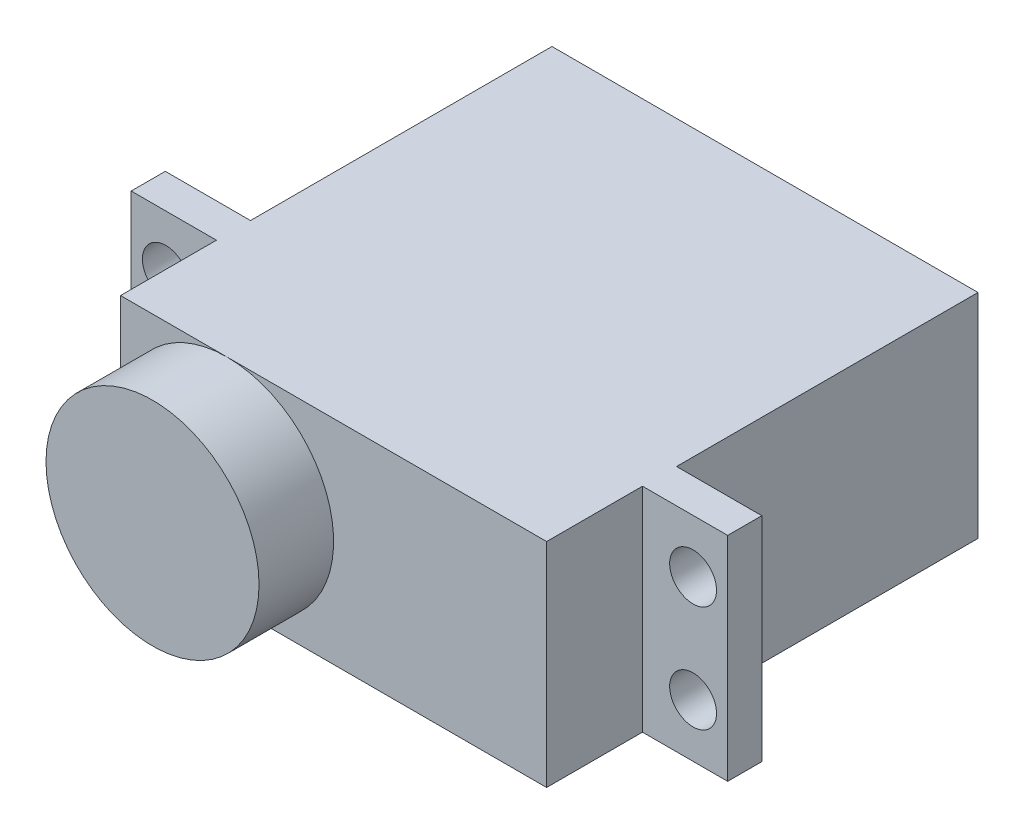
SolidWorks part; units mm, degrees
ref_plane "Front Plane" through (0, 0, 0) normal (0, 0, 1) x (1, 0, 0)
ref_plane "Top Plane" through (0, 0, 0) normal (0, 1, 0) x (1, 0, 0)
ref_plane "Right Plane" through (0, 0, 0) normal (1, 0, 0) x (0, 0, -1)
sketch "Sketch1" plane through (0, 0, 0) normal (0, 0, 1) x (1, 0, 0)
  line L1 (-20, 10) -> (20, 10)
  line L2 (-20, 10) -> (-20, -10)
  line L3 (-20, -10) -> (20, -10)
  line L4 (20, 10) -> (20, -10)
  line L5 (-20, 10) -> (20, -10) construction
  line L6 (-20, -10) -> (20, 10) construction
  point P0 (0, 0)
extrude "Boss-Extrude1" add sketch "Sketch1" against normal blind 40.5 contours L1 L4 L3 L2
sketch "Sketch2" plane through (0, 0, 0) normal (0, 0, 1) x (1, 0, 0)
  line L0 (-20, 10) -> (20, 10) construction
  line L1 (-20, 10) -> (-20, -10) construction
  circle A0 centre (-10, 0) radius 10
  dimension "D1" = 10
  dimension "D2" = 10
extrude "Boss-Extrude2" add sketch "Sketch2" along normal blind 7 contours A0
sketch "Sketch3" plane through (-20, 0, 0) normal (-1, 0, 0) x (0, 0, 1)
  line L0 (-40.5, 10) -> (0, 10) construction
  line L1 (-9, 10) -> (-12.2, 10)
  line L2 (-9, 10) -> (-9, -10)
  line L3 (-9, -10) -> (-12.2, -10)
  line L4 (-12.2, 10) -> (-12.2, -10)
  line L5 (-40.5, -10) -> (0, -10) construction
  dimension "D1" = 9
extrude "Boss-Extrude3" add sketch "Sketch3" along normal blind 8 contours L1 L4 L3 L2
sketch "Sketch4" plane through (20, 0, 0) normal (1, 0, 0) x (0, 0, -1)
  line L0 (40.5, 10) -> (0, 10) construction
  line L1 (9, 10) -> (12.2, 10)
  line L2 (9, 10) -> (9, -10)
  line L3 (9, -10) -> (12.2, -10)
  line L4 (12.2, 10) -> (12.2, -10)
  line L5 (40.5, -10) -> (0, -10) construction
  dimension "D1" = 9
extrude "Boss-Extrude4" add sketch "Sketch4" along normal blind 8 contours L2 L3 L4 L1
sketch "Sketch6" plane through (0, 0, -9) normal (0, 0, 1) x (1, 0, 0)
  circle A0 centre (-24.75, 5) radius 2.2
  circle A1 centre (-24.75, -5) radius 2.2
  dimension "D1" = 10
  dimension "D2" = 5
  dimension "D3" = 24.75
  dimension "D4" = 0
sketch "Sketch8" plane through (0, 0, -9) normal (0, 0, 1) x (1, 0, 0)
  circle A0 centre (24.75, 5) radius 2.2
  circle A1 centre (24.75, -5) radius 2.2
  point P4 (0, 0)
  dimension "D1" = 10
  dimension "D2" = 5
  dimension "D3" = 24.75
extrude "Cut-Extrude1" cut sketch "Sketch6" against normal blind 8
extrude "Cut-Extrude3" cut sketch "Sketch8" against normal blind 8 contours A0 | A1
